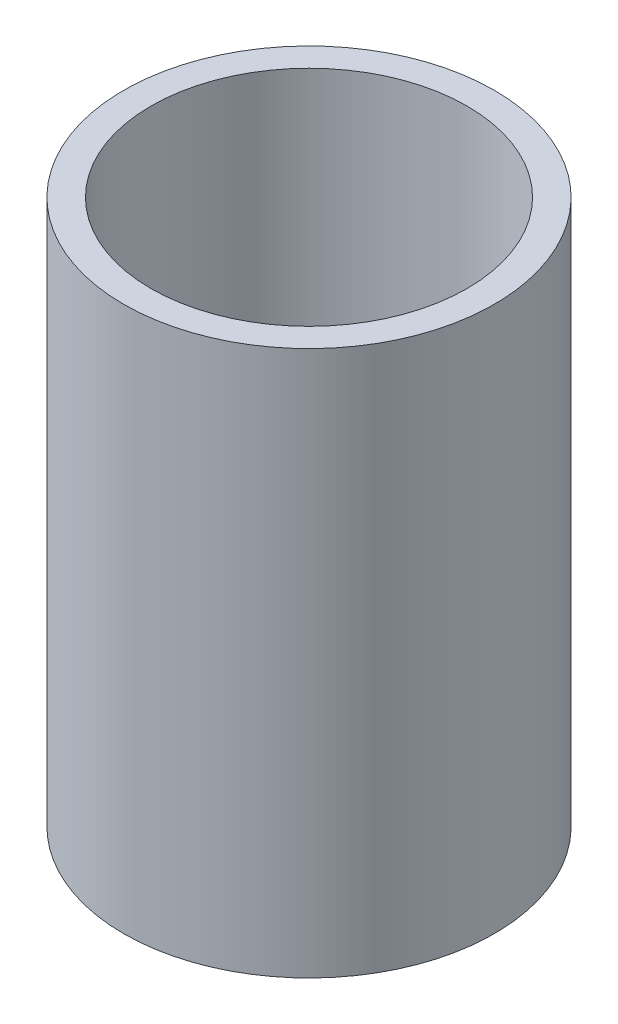
SolidWorks part; units mm, degrees
ref_plane "Front Plane" through (0, 0, 0) normal (0, 0, 1) x (1, 0, 0)
ref_plane "Top Plane" through (0, 0, 0) normal (0, 1, 0) x (1, 0, 0)
ref_plane "Right Plane" through (0, 0, 0) normal (1, 0, 0) x (0, 0, -1)
sketch "Sketch1" plane through (0, 0, 0) normal (0, 1, 0) x (1, 0, 0)
  circle A0 centre (0, 0) radius 34
  dimension "D1" = 68
extrude "Boss-Extrude1" add sketch "Sketch1" along normal blind 100
sketch "Sketch2" plane through (0, 100, 0) normal (0, 1, 0) x (1, 0, 0)
  circle A0 centre (0, 0) radius 29
  dimension "D1" = 58
extrude "Cut-Extrude1" cut sketch "Sketch2" against normal blind 100
